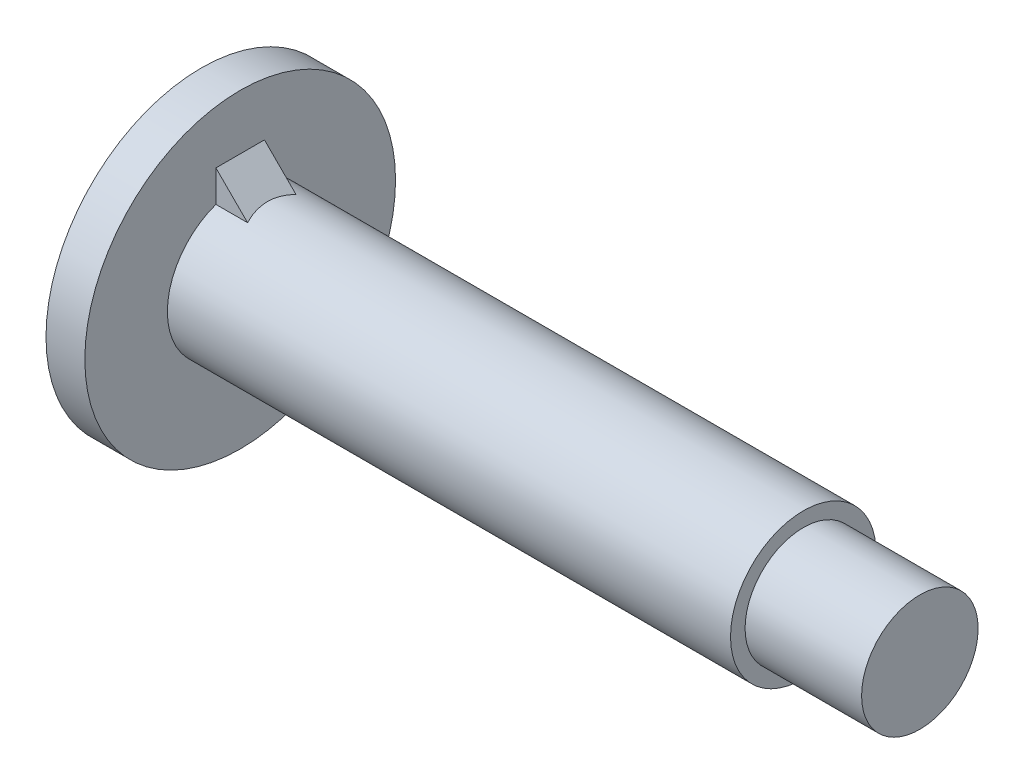
SolidWorks part; units mm, degrees
ref_plane "Alzado" through (0, 0, 0) normal (0, 0, 1) x (1, 0, 0)
ref_plane "Planta" through (0, 0, 0) normal (0, 1, 0) x (1, 0, 0)
ref_plane "Vista lateral" through (0, 0, 0) normal (1, 0, 0) x (0, 0, -1)
sketch "Croquis1" plane through (0, 0, 0) normal (0, 0, 1) x (1, 0, 0)
  line L0 (0, 0) -> (37, 0)
  line L1 (37, 0) -> (37, 3)
  line L2 (37, 3) -> (31, 3)
  line L3 (31, 3) -> (31, 3.75)
  line L4 (31, 3.75) -> (2, 3.75)
  line L5 (2, 3.75) -> (2, 8)
  line L6 (2, 8) -> (0, 8)
  line L7 (0, 8) -> (0, 0)
  dimension "D1" = 3
  dimension "D2" = 3.75
  dimension "D3" = 8
  dimension "D4" = 2
  dimension "D5" = 37
  dimension "D6" = 6
revolve "Revolución1" add sketch "Croquis1" angle 360 about L0
sketch "Croquis2" plane through (0, 0, 0) normal (0, 0, 1) x (1, 0, 0)
  line L0 (2, 5.1642) -> (3.4142, 3.75)
  line L1 (2, -8) -> (2, 8) construction
  line L2 (31, 3.75) -> (2, 3.75) construction
  line L3 (3.4142, 3.75) -> (5.4262, 1.738)
  line L4 (5.4262, 1.738) -> (0.7125, 1.738)
  line L5 (0.7125, 1.738) -> (0.7125, 6.4517)
  line L6 (2, 5.1642) -> (0.7125, 6.4517)
  point P9 (5.4262, 1.738)
  point P10 (0.7125, 6.4517)
  dimension "D1" = 45
  dimension "D2" = 2
extrude "Saliente-Extruir1" add sketch "Croquis2" along normal mid plane 2.5
